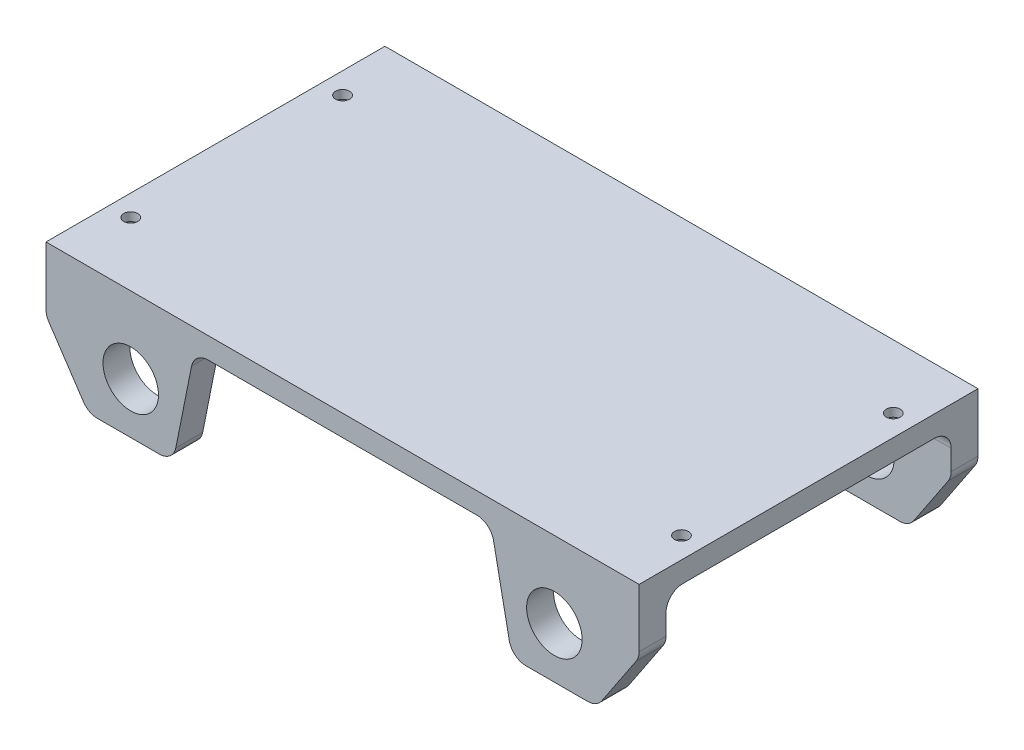
SolidWorks part; units mm, degrees
ref_plane "Alzado" through (0, 0, 0) normal (0, 0, 1) x (1, 0, 0)
ref_plane "Planta" through (0, 0, 0) normal (0, 1, 0) x (1, 0, 0)
ref_plane "Vista lateral" through (0, 0, 0) normal (1, 0, 0) x (0, 0, -1)
sketch "Croquis1" plane through (0, 0, 0) normal (0, 0, 1) x (1, 0, 0)
  line L1 (-70, 15) -> (70, 15)
  line L2 (-70, 15) -> (-70, -15)
  line L3 (-70, -15) -> (70, -15)
  line L4 (70, 15) -> (70, -15)
  line L5 (-70, 15) -> (70, -15) construction
  line L6 (-70, -15) -> (70, 15) construction
  point P0 (0, 0)
  dimension "D1" = 140
  dimension "D2" = 30
extrude "Saliente-Extruir1" add sketch "Croquis1" along normal mid plane 80
sketch "Croquis2" plane through (0, 0, 0) normal (1, 0, 0) x (0, 0, -1)
  line L0 (-33.65, 10) -> (33.65, 10)
  line L2 (-33.65, 10) -> (-33.65, -15)
  line L3 (-40, -15) -> (40, -15) construction
  line L4 (33.65, 10) -> (33.65, -15)
  line L6 (33.65, -15) -> (-33.65, -15)
  line L7 (-40, 15) -> (40, 15) construction
  line L8 (-40, -15) -> (-40, 15) construction
  point P2 (0, 10)
  dimension "D1" = 6.35
  dimension "D2" = 5
extrude "Cortar-Extruir1" cut sketch "Croquis2" against normal through all both and the other way through all
sketch "Croquis3" plane through (0, 0, 40) normal (0, 0, 1) x (1, 0, 0)
  line L0 (-50, -3) -> (50, -3) construction
  circle A0 centre (50, -3) radius 6.55
  circle A1 centre (-50, -3) radius 6.55
  point P2 (0, -3)
  dimension "D1" = 13.1
  dimension "D2" = 100
  dimension "D3" = 3
extrude "Cortar-Extruir2" cut sketch "Croquis3" against normal blind 80
sketch "Croquis4" plane through (0, 10, 0) normal (0, -1, 0) x (1, 0, 0)
  line L0 (-65, 25) -> (-65, -25) construction
  circle A0 centre (-65, 25) radius 1.651
  circle A1 centre (-65, -25) radius 1.651
  point P5 (0, 0)
  point P6 (-65, 0)
  point P10 (0, 0)
  dimension "D1" = 3.302
  dimension "D2" = 50
  dimension "D3" = 65
extrude "Cortar-Extruir3" cut sketch "Croquis4" against normal up to next
sketch "Croquis5" plane through (0, 10, 0) normal (0, -1, 0) x (1, 0, 0)
  circle A0 centre (-65, 25) radius 3.5
  circle A2 centre (-65, -25) radius 3.5
  circle A3 centre (-65, -25) radius 1.651
  circle A5 centre (-65, 25) radius 1.651
  circle A6 centre (-65, 25) radius 1.651 construction
  circle A8 centre (-65, -25) radius 1.651 construction
  dimension "D1" = 7
extrude "Cortar-Extruir4" cut sketch "Croquis5" against normal blind 3
sketch "Croquis9" plane through (0, 0, 0) normal (0, 0, 1) x (1, 0, 0)
  line L0 (-40, -15) -> (-35, 10)
  line L1 (-70, -15) -> (70, -15) construction
  line L2 (-35, 10) -> (35, 10)
  line L3 (35, 10) -> (40, -15)
  line L4 (-40, -15) -> (40, -15)
  line L5 (70, 15) -> (-70, 15) construction
  line L6 (-70, 0) -> (-60, -15)
  line L7 (-70, 15) -> (-70, -15) construction
  line L8 (-60, -15) -> (-70, -15)
  line L9 (-70, -15) -> (-70, 0)
  line L10 (70, 0) -> (60, -15)
  line L11 (70, -15) -> (70, 15) construction
  line L12 (60, -15) -> (70, -15)
  line L13 (70, -15) -> (70, 0)
  point P4 (0, 10)
  dimension "D1" = 70
  dimension "D2" = 80
  dimension "D3" = 5
  dimension "D4" = 10
  dimension "D5" = 15
  dimension "D6" = 15
  dimension "D7" = 10
extrude "Cortar-Extruir5" cut sketch "Croquis9" against normal through all both and the other way through all
mirror "Simetría4" about plane through (0, 0, 0) normal (1, 0, 0) of "Cortar-Extruir4", "Cortar-Extruir3"
fillet "Redondeo1" radius 4 20 edges at (-40, -15, 36.825) (-60, -15, 36.825) (-70, 0, 36.825) (40, -15, 36.825) (60, -15, 36.825) (70, 0, 36.825) (70, 0, -36.825) (60, -15, -36.825) (40, -15, -36.825) (-40, -15, -36.825) (-60, -15, -36.825) (-70, 0, -36.825) (-52.5, 10, -33.65) (52.5, 10, -33.65) (-35, 10, -36.825) (35, 10, -36.825) (-35, 10, 36.825) (35, 10, 36.825) (52.5, 10, 33.65) (-52.5, 10, 33.65)
